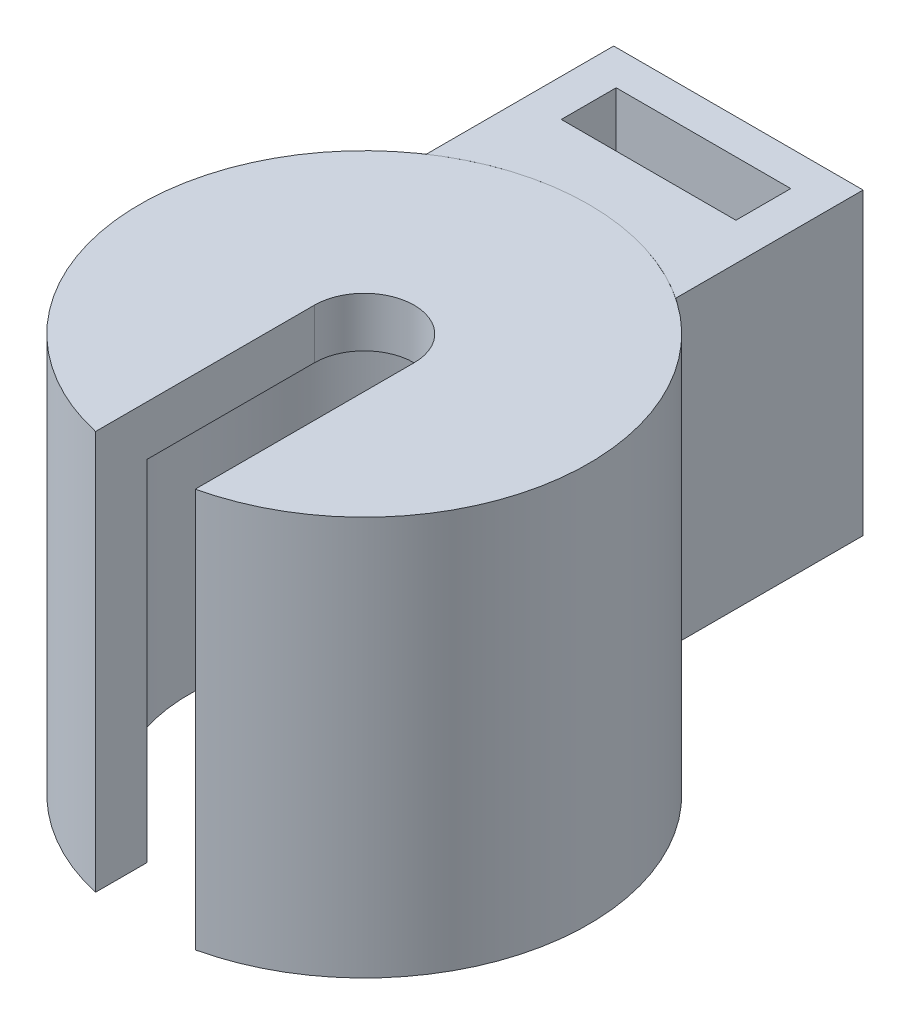
SolidWorks part; units mm, degrees
ref_plane "Front Plane" through (0, 0, 0) normal (0, 0, 1) x (1, 0, 0)
ref_plane "Top Plane" through (0, 0, 0) normal (0, 1, 0) x (1, 0, 0)
ref_plane "Right Plane" through (0, 0, 0) normal (1, 0, 0) x (0, 0, -1)
sketch "Sketch1" plane through (0, 0, 0) normal (0, 1, 0) x (1, 0, 0)
  line L1 (-1, 0) -> (1, 0)
  line L2 (-1, 0) -> (-1, -6.3229)
  line L3 (-1, -6.3229) -> (1, -6.3229)
  line L4 (1, 0) -> (1, -6.3229)
  circle A0 centre (0, 0) radius 3.5
  circle A1 centre (0, 0) radius 4.5
  circle A2 centre (0, 0) radius 1
  dimension "D1" = 7
  dimension "D2" = 9
  dimension "D3" = 2
  dimension "D4" = 2
extrude "Boss-Extrude1" add sketch "Sketch1" along normal blind 7 contours L4 A1 L2 A0
sketch "Sketch2" plane through (0, 7, 0) normal (0, 1, 0) x (1, 0, 0)
  line L1 (-1, 0) -> (1, 0)
  line L2 (-1, 0) -> (-1, -6.0985)
  line L3 (-1, -6.0985) -> (1, -6.0985)
  line L4 (1, 0) -> (1, -6.0985)
  circle A0 centre (0, 0) radius 5.25
  circle A1 centre (0, 0) radius 1
  line M7 (1, -3.3541) -> (1, -4.3875)
  arc M8 (1, -4.3875) -> (-1, -4.3875) centre (0, 0) ccw
  line M9 (-1, -4.3875) -> (-1, -3.3541)
  arc M10 (-1, -3.3541) -> (1, -3.3541) centre (0, 0) cw
  dimension "D1" = 2
  dimension "D2" = 2
extrude "Boss-Extrude2" add sketch "Sketch2" along normal blind 1 contours A1 L4 L2 M10 | M10 M7 M8 M9
sketch "Sketch3" plane through (0, 0, 0) normal (1, 0, 0) x (0, 0, -1)
  line L0 (4.5, 8) -> (4.5, 7.999)
  line L1 (4.5, 0) -> (4.5, 8) construction
  line L2 (4.5, 7.999) -> (3.5, 7.999)
  line L4 (3.5, 7.999) -> (7.5, 7.999)
  line L5 (3.5, 7.999) -> (3.5, 1.999)
  line L6 (3.5, 1.999) -> (7.5, 1.999)
  line L7 (7.5, 7.999) -> (7.5, 1.999)
  dimension "D1" = 0.001
  dimension "D2" = 1
  dimension "D3" = 6
  dimension "D4" = 4
extrude "Boss-Extrude3" add sketch "Sketch3" along normal blind 2.5 and the other way blind 2.5 contours L7 L4 L2 L5 L6
sketch "Sketch4" plane through (0, 7.999, 0) normal (0, 1, 0) x (1, 0, 0)
  line L0 (0, 7.5) -> (0, 6.8)
  line L1 (-2.5, 7.5) -> (2.5, 7.5) construction
  line L2 (0, -4.4) -> (0, 4.4) construction
  line L3 (0, 6.8) -> (1.75, 6.8)
  line L5 (1.75, 6.8) -> (-1.75, 6.8)
  line L6 (1.75, 6.8) -> (1.75, 5.7)
  line L7 (1.75, 5.7) -> (-1.75, 5.7)
  line L8 (-1.75, 6.8) -> (-1.75, 5.7)
  dimension "D1" = 0.7
  dimension "D2" = 1.75
  dimension "D3" = 3.5
  dimension "D4" = 1.1
extrude "Cut-Extrude1" cut sketch "Sketch4" against normal blind 7 contours L5 L8 L7 L6 L3
